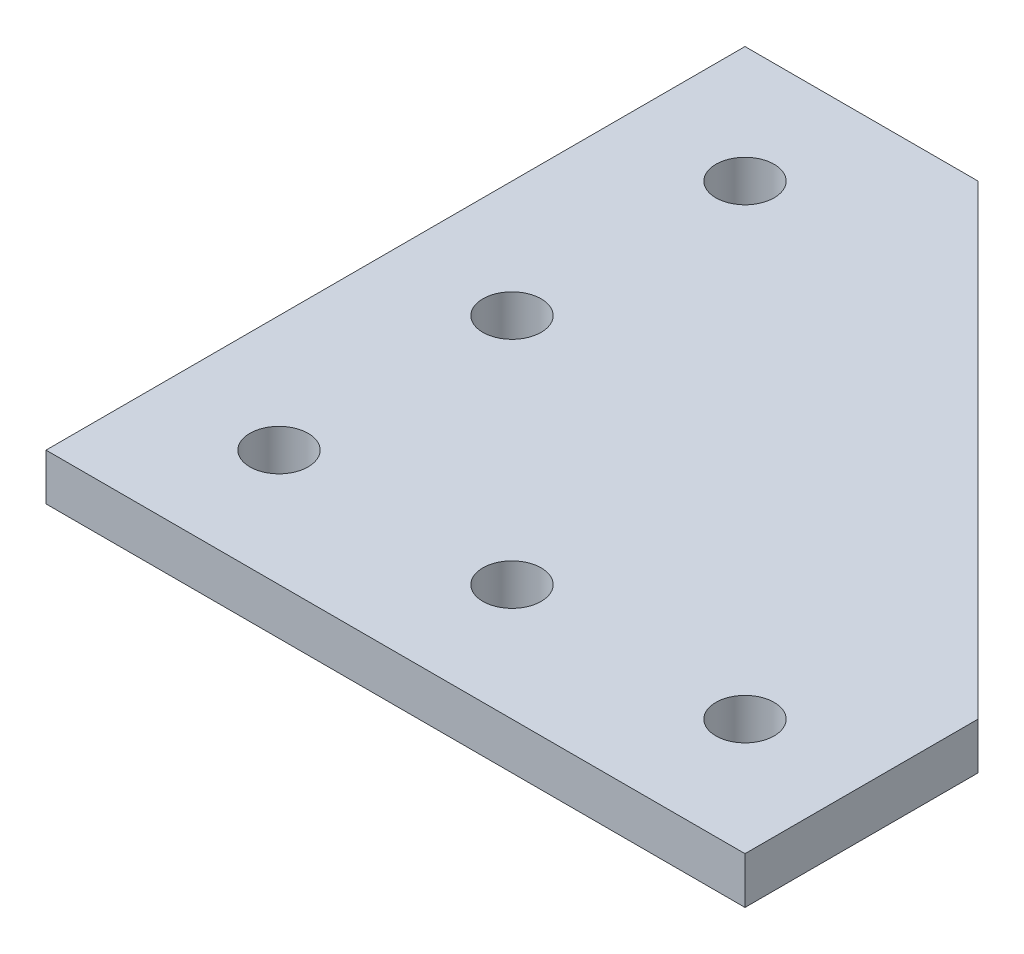
SolidWorks part; units mm, degrees
material "6061 Alloy"
ref_plane "Front Plane" through (0, 0, 0) normal (0, 0, 1) x (1, 0, 0)
ref_plane "Top Plane" through (0, 0, 0) normal (0, 1, 0) x (1, 0, 0)
ref_plane "Right Plane" through (0, 0, 0) normal (1, 0, 0) x (0, 0, -1)
sketch "Sketch1" plane through (0, 0, 0) normal (0, 1, 0) x (1, 0, 0)
  line L0 (-10, -10) -> (-10, 50)
  line L5 (0, 0) -> (-10, 0) construction
  line L6 (0, 0) -> (0, -10) construction
  line L7 (0, -10) -> (-10, -10) construction
  line L8 (-10, 0) -> (-10, -10) construction
  line L9 (-10, 50) -> (10, 50)
  line L10 (-10, -10) -> (50, -10)
  line L11 (50, -10) -> (50, 10)
  line L12 (50, 10) -> (10, 50)
  dimension "D1" = 10
  dimension "D2" = 10
extrude "Boss-Extrude1" add sketch "Sketch1" along normal mid plane 4
sketch "Sketch3" plane through (0, 0, 0) normal (0, 1, 0) x (1, 0, 0)
  circle A0 centre (0, 0) radius 2.5
  circle A1 centre (20, 0) radius 2.5
  circle A2 centre (40, 0) radius 2.5
  circle A3 centre (0, 20) radius 2.5
  circle A4 centre (0, 40) radius 2.5
extrude "Cut-Extrude1" cut sketch "Sketch3" against normal through all both and the other way through all
